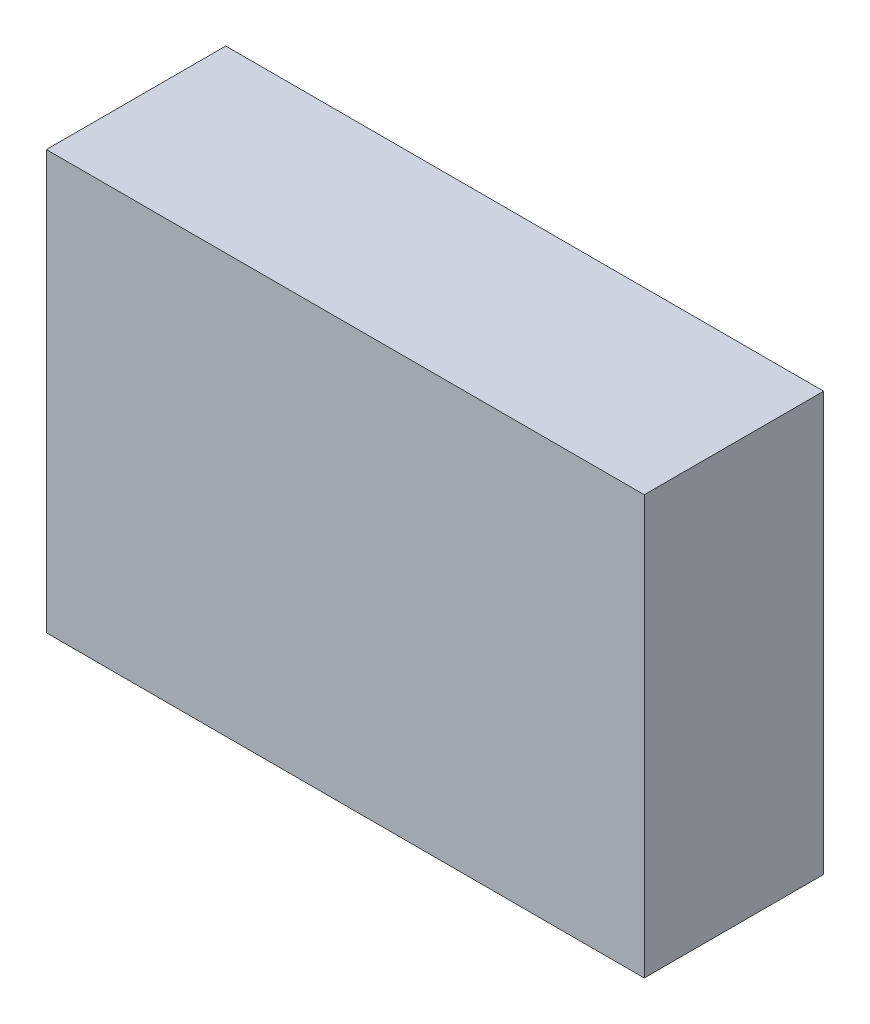
SolidWorks part; units mm, degrees
material "1023 Carbon Steel Sheet (SS)"
ref_plane "Front Plane" through (0, 0, 0) normal (0, 0, 1) x (1, 0, 0)
ref_plane "Top Plane" through (0, 0, 0) normal (0, 1, 0) x (1, 0, 0)
ref_plane "Right Plane" through (0, 0, 0) normal (1, 0, 0) x (0, 0, -1)
sketch "Sketch1" plane through (0, 0, 0) normal (0, 0, 1) x (1, 0, 0)
  line L1 (0, 0) -> (1000, 0)
  line L2 (0, 0) -> (0, 700)
  line L3 (0, 700) -> (1000, 700)
  line L4 (1000, 0) -> (1000, 700)
  dimension "D1" = 1000
  dimension "D2" = 700
extrude "Boss-Extrude1" add sketch "Sketch1" along normal blind 300
